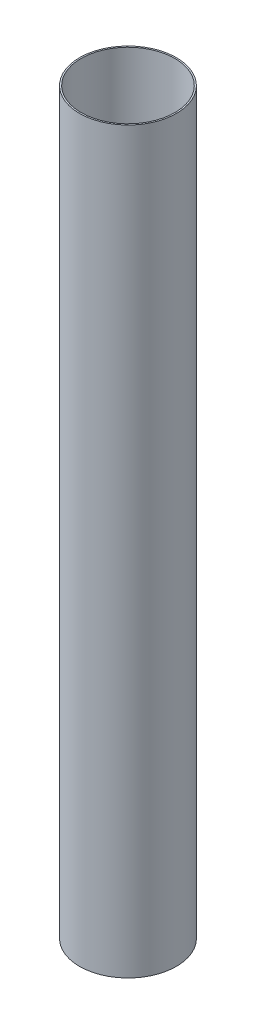
SolidWorks part; units mm, degrees
material "AISI 1020"
ref_plane "Plano frontal" through (0, 0, 0) normal (0, 0, 1) x (1, 0, 0)
ref_plane "Plano superior" through (0, 0, 0) normal (0, 1, 0) x (1, 0, 0)
ref_plane "Plano direito" through (0, 0, 0) normal (1, 0, 0) x (0, 0, -1)
sketch "Esboço2" plane through (0, 0, 0) normal (0, 1, 0) x (1, 0, 0)
  circle A0 centre (0, 0) radius 19
  circle A1 centre (0, 0) radius 18.42
  dimension "D1" = 38
  dimension "D2" = 36.84
extrude "Ressalto-extrusão1" add sketch "Esboço2" along normal blind 290
